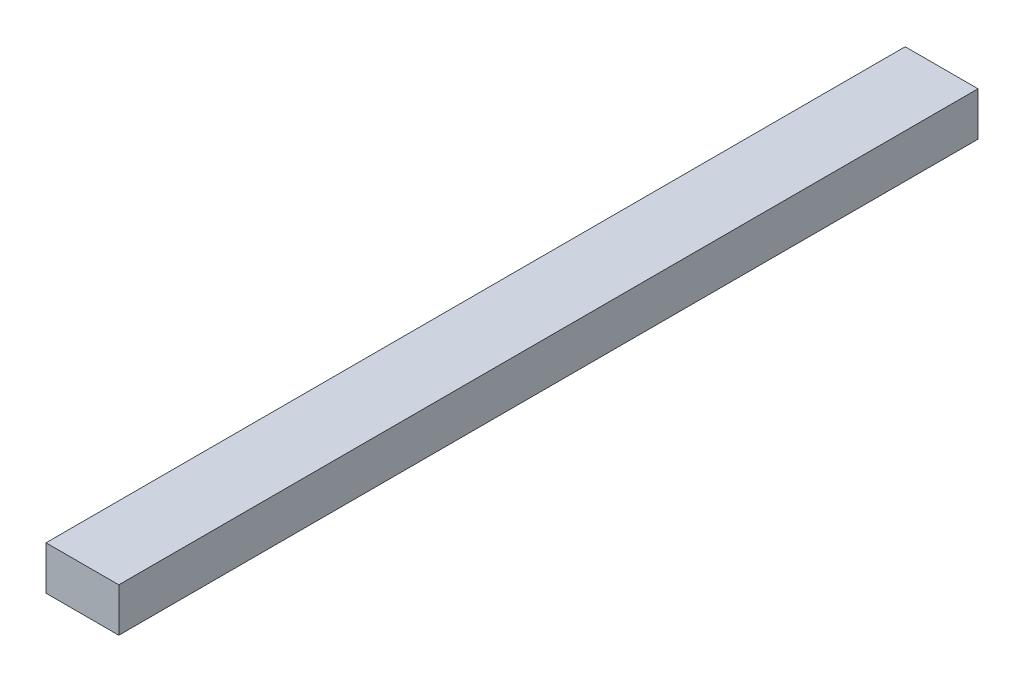
SolidWorks part; units mm, degrees
material "Kiefer"
ref_plane "Ebene vorne" through (0, 0, 0) normal (0, 0, 1) x (1, 0, 0)
ref_plane "Ebene oben" through (0, 0, 0) normal (0, 1, 0) x (1, 0, 0)
ref_plane "Ebene rechts" through (0, 0, 0) normal (1, 0, 0) x (0, 0, -1)
sketch "Skizze1" plane through (0, 0, 0) normal (0, 0, 1) x (1, 0, 0)
  line L0 (0, 0) -> (0, 40.512) construction
  line L2 (50, 30) -> (-50, 30)
  line L3 (50, 30) -> (50, -30)
  line L4 (50, -30) -> (-50, -30)
  line L5 (-50, 30) -> (-50, -30)
  line L6 (50, 30) -> (-50, -30) construction
  line L7 (50, -30) -> (-50, 30) construction
  dimension "D1" = 100
  dimension "D2" = 60
extrude "Aufsatz-Linear austragen1" add sketch "Skizze1" along normal mid plane 1180
